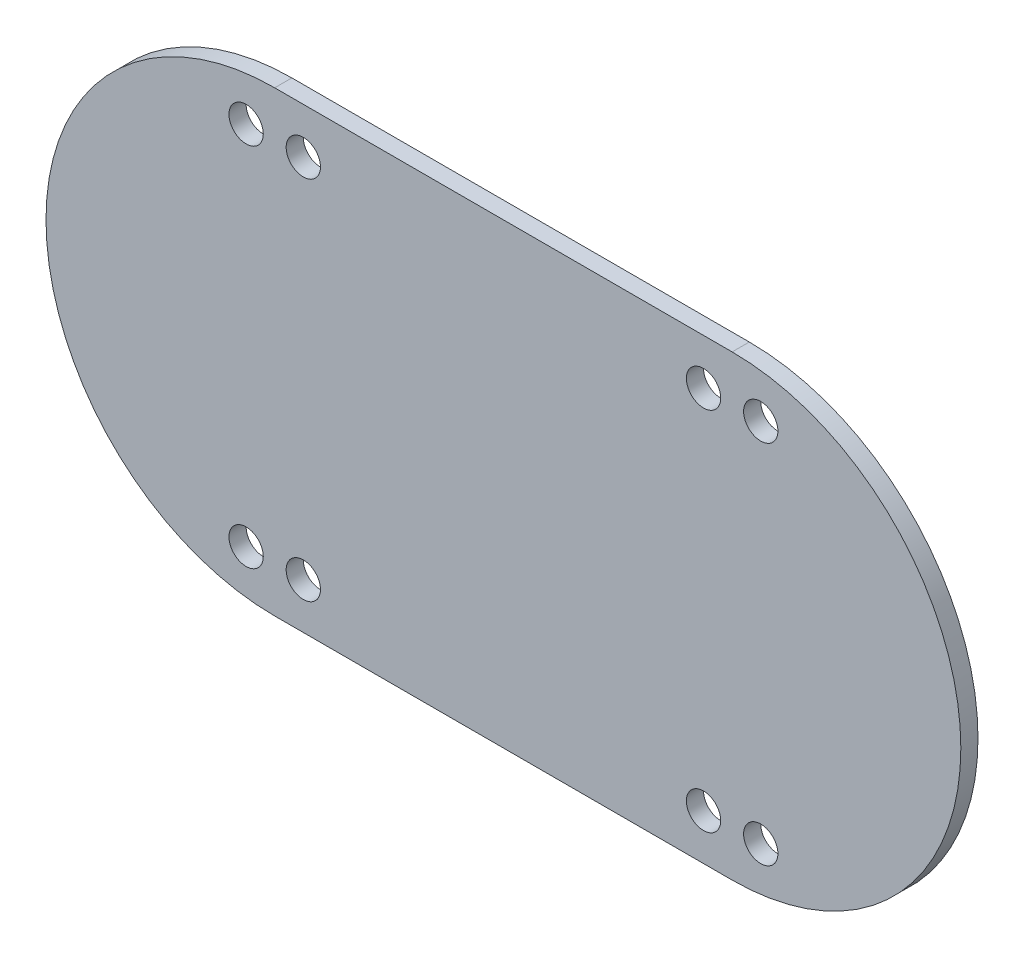
SolidWorks part; units mm, degrees
ref_plane "Front Plane" through (0, 0, 0) normal (0, 0, 1) x (1, 0, 0)
ref_plane "Top Plane" through (0, 0, 0) normal (0, 1, 0) x (1, 0, 0)
ref_plane "Right Plane" through (0, 0, 0) normal (1, 0, 0) x (0, 0, -1)
sketch "Sketch1" plane through (0, 0, 0) normal (0, 0, 1) x (1, 0, 0)
  line L1 (40, 40.2192) -> (-40, 40.2192)
  line L3 (40, -39.7808) -> (-40, -39.7808)
  arc A0 (40, -39.7808) -> (40, 40.2192) centre (40, 0.2192) ccw
  arc A1 (-40, 40.2192) -> (-40, -39.7808) centre (-40, 0.2192) ccw
  circle A2 centre (45, 32.2192) radius 3
  circle A3 centre (45, -31.7808) radius 3
  circle A4 centre (-45, 32.2192) radius 3
  circle A5 centre (-45, -31.7808) radius 3
  circle A6 centre (35, 32.2192) radius 3
  circle A7 centre (-35, 32.2192) radius 3
  circle A8 centre (-35, -31.7808) radius 3
  circle A9 centre (35, -31.7808) radius 3
  point P0 (0, 0)
  dimension "D5" = 6
  dimension "D6" = 6
  dimension "D7" = 6
  dimension "D8" = 6
  dimension "D17" = 6
  dimension "D18" = 6
  dimension "D19" = 6
  dimension "D20" = 6
  dimension "D1" = 80
  dimension "D2" = 80
extrude "Boss-Extrude1" add sketch "Sketch1" along normal blind 3
